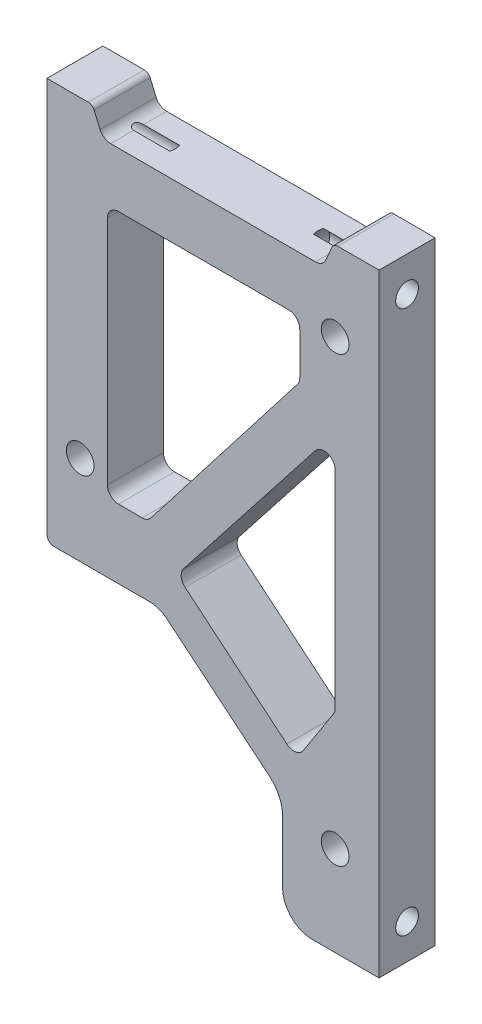
SolidWorks part; units mm, degrees
ref_plane "Piano frontale" through (0, 0, 0) normal (0, 0, 1) x (1, 0, 0)
ref_plane "Piano superiore" through (0, 0, 0) normal (0, 1, 0) x (1, 0, 0)
ref_plane "Piano destro" through (0, 0, 0) normal (1, 0, 0) x (0, 0, -1)
sketch "Schizzo1" plane through (0, 0, 0) normal (0, 0, 1) x (1, 0, 0)
  line L0 (15.136, 57.9901) -> (33.6079, 57.9901)
  line L1 (9.3919, 60.2186) -> (39.3519, 60.2186)
  line L2 (9.3919, 60.2186) -> (9.3919, 4.9186)
  line L3 (9.3919, 4.9186) -> (39.3519, 4.9186)
  line L4 (39.3519, 60.2186) -> (39.3519, 4.9186)
  line L5 (24.3719, 60.2186) -> (24.3719, 4.9186) construction
  line L6 (14.1898, 58.612) -> (13.6447, 59.8738)
  line L7 (34.554, 58.612) -> (35.0991, 59.8738)
  line L8 (10.0258, 23.964) -> (18.6757, 23.964)
  line L9 (20.1991, 23.4153) -> (29.4267, 15.7774)
  line L10 (30.6515, 13.1737) -> (30.6515, 7.6106)
  line L11 (31.1965, 53.0372) -> (15.8448, 53.0372)
  line L12 (14.8448, 52.0372) -> (14.8448, 31.1822)
  line L13 (15.8448, 30.1822) -> (17.9856, 30.1822)
  line L14 (18.776, 30.5696) -> (31.9869, 47.6146)
  line L15 (32.1965, 48.2272) -> (32.1965, 52.0372)
  line L16 (21.8582, 26.6856) -> (31.0315, 19.0354)
  line L17 (32.5125, 19.2616) -> (35.2317, 23.4795)
  line L18 (35.3912, 24.0214) -> (35.3912, 42.6221)
  line L19 (33.6042, 43.2391) -> (21.7117, 28.0706)
  line L20 (35.3912, 53.0372) -> (35.3912, 13.0372) construction
  arc A0 (15.136, 57.9901) -> (14.1898, 58.612) centre (15.136, 59.0208) cw
  arc A1 (13.6447, 59.8738) -> (13.1202, 60.2186) centre (13.1202, 59.6472) ccw
  arc A2 (35.0991, 59.8738) -> (35.6236, 60.2186) centre (35.6236, 59.6472) cw
  arc A3 (33.6079, 57.9901) -> (34.554, 58.612) centre (33.6079, 59.0208) ccw
  arc A4 (18.6757, 23.964) -> (20.1991, 23.4153) centre (18.6757, 21.5749) cw
  arc A5 (29.4267, 15.7774) -> (30.6515, 13.1737) centre (27.2716, 13.1737) cw
  arc A6 (30.6515, 7.6106) -> (33.3435, 4.9186) centre (33.3435, 7.6106) ccw
  arc A7 (10.0258, 23.964) -> (9.3919, 24.5979) centre (10.0258, 24.5979) cw
  arc A8 (35.2317, 23.4795) -> (35.3912, 24.0214) centre (34.3912, 24.0214) ccw
  arc A9 (31.0315, 19.0354) -> (32.5125, 19.2616) centre (31.672, 19.8034) ccw
  arc A10 (21.8582, 26.6856) -> (21.7117, 28.0706) centre (22.4986, 27.4536) cw
  arc A11 (35.3912, 42.6221) -> (33.6042, 43.2391) centre (34.3912, 42.6221) ccw
  arc A12 (31.9869, 47.6146) -> (32.1965, 48.2272) centre (31.1965, 48.2272) ccw
  arc A13 (17.9856, 30.1822) -> (18.776, 30.5696) centre (17.9856, 31.1822) ccw
  arc A14 (14.8448, 31.1822) -> (15.8448, 30.1822) centre (15.8448, 31.1822) ccw
  arc A15 (31.1965, 53.0372) -> (32.1965, 52.0372) centre (31.1965, 52.0372) cw
  arc A16 (15.8448, 53.0372) -> (14.8448, 52.0372) centre (15.8448, 52.0372) ccw
  circle A17 centre (35.3912, 53.0372) radius 1.4023 construction
  circle A18 centre (12.3912, 32.0372) radius 1.4022 construction
  circle A19 centre (35.3912, 13.0372) radius 1.3846 construction
  point P19 (24.3719, 57.9901)
  dimension "D3" = 1
  dimension "D1" = 29.96
  dimension "D2" = 55.3
  dimension "D4" = 40
  dimension "D5" = 21
  dimension "D6" = 23
extrude "Estrusione-Estrusione1" add sketch "Schizzo1" along normal blind 5.05 contours A7 L8 A4 L9 A5 L10 A6 L3 L4 L1 A2 L7 A3 L0 A0 L6 A1 L2 A16 L11 A15 L15 A12 L14 A13 L13 A14 L12 A11 L18 A8 L17 A9 L16 A10 L19
hole_wizard "Foro filettato M3x0.5-1" positions "Schizzo3" profile "Schizzo2" tap size "M3x0.5" standard "Ansi Metric" end condition through all
sketch "Schizzo3" plane through (0, 0, 5.05) normal (0, 0, 1) x (1, 0, 0)
  point P0 (35.3912, 53.0372)
  point P2 (12.3912, 32.0372)
  point P4 (35.3912, 13.0372)
sketch "Schizzo2" plane through (35.3912, 53.0372, 5.05) normal (1, 0, 0) x (0, -1, 0)
  line L0 (0, 0) -> (0, 5.05)
  line L1 (0, 5.05) -> (1.25, 5.05)
  line L2 (1.25, 5.05) -> (1.25, 0)
  line L5 (1.25, 0) -> (0, 0)
  line L11 (0, -6.35) -> (0, 107.95) construction
  dimension "Thru Tap Drill Dia." = 2.5
  dimension "Thru Tap Drill Depth" = 5.05
cosmetic thread "Filettatura del foro1" parameters "D2"=3
cosmetic thread "Filettatura del foro2" parameters "D2"=3
cosmetic thread "Filettatura del foro3" parameters "D2"=3
hole_wizard "Foro filettato M2.5x0.45-1" positions "Schizzo5" profile "Schizzo4" tap size "M2.5x0.45" standard "Ansi Metric"
sketch "Schizzo5" plane through (39.3519, 0, 0) normal (1, 0, 0) x (0, 0, -1)
  line L0 (-2.525, 8.0686) -> (-2.525, 57.0686) construction
  line L1 (-5.05, 60.2186) -> (0, 60.2186) construction
  line L3 (-5.05, 4.9186) -> (0, 60.2186) construction
  point P0 (-2.525, 57.0686)
  point P2 (-2.525, 8.0686)
  point P10 (-2.525, 60.2186)
  point P19 (-2.525, 32.5686)
  dimension "D1" = 49
sketch "Schizzo4" plane through (39.3519, 57.0686, 2.525) normal (0, 1, 0) x (0, 0, -1)
  line L0 (0, 0) -> (0, 8.6159)
  line L1 (0, 8.6159) -> (1.025, 8)
  line L2 (1.025, 8) -> (1.025, 0)
  line L5 (1.025, 0) -> (0, 0)
  line L10 (0, 8.6159) -> (-1.025, 8) construction
  line L11 (0, -6.35) -> (0, 107.95) construction
  dimension "Tap Drill Dia." = 2.05
  dimension "Tap Drill Depth" = 8
  dimension "Drill Angle" = 118
cosmetic thread "Filettatura del foro4" parameters "D1"=8, "D2"=3
cosmetic thread "Filettatura del foro5" parameters "D1"=8, "D2"=3
hole_wizard "Foro filettato M2.5x0.45-2" positions "Schizzo7" profile "Schizzo6" tap size "M2.5x0.45" standard "Ansi Metric"
sketch "Schizzo7" plane through (9.3919, 0, 0) normal (-1, 0, 0) x (0, 0, 1)
  line L0 (2.525, 27.0686) -> (2.525, 57.0686) construction
  line L1 (5.05, 60.2186) -> (0, 60.2186) construction
  arc A0 (2.0763, 57.9901) -> (2.9737, 57.9901) centre (2.525, 57.0686) ccw construction
  point P0 (2.525, 57.0686)
  point P2 (2.525, 27.0686)
  point P9 (2.525, 60.2186)
  dimension "D1" = 30
sketch "Schizzo6" plane through (9.3919, 57.0686, 2.525) normal (0, 1, 0) x (0, 0, 1)
  line L0 (0, 0) -> (0, 9.6159)
  line L1 (0, 9.6159) -> (1.025, 9)
  line L2 (1.025, 9) -> (1.025, 0)
  line L5 (1.025, 0) -> (0, 0)
  line L10 (0, 9.6159) -> (-1.025, 9) construction
  line L11 (0, -6.35) -> (0, 107.95) construction
  dimension "Tap Drill Dia." = 2.05
  dimension "Tap Drill Depth" = 9
  dimension "Drill Angle" = 118
cosmetic thread "Filettatura del foro7" parameters "D1"=9, "D2"=2.5
cosmetic thread "Filettatura del foro8" parameters "D1"=9, "D2"=2.5
